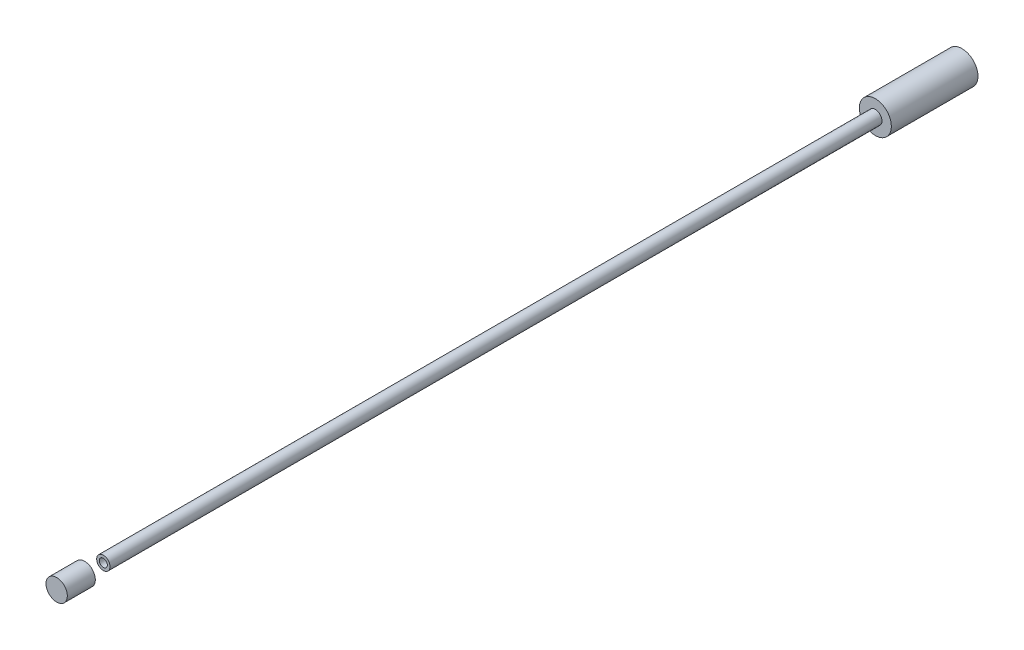
SolidWorks part; units mm, degrees
material "AISI 316 Annealed Stainless Steel Bar (SS)"
ref_plane "Front Plane" through (0, 0, 0) normal (0, 0, 1) x (1, 0, 0)
ref_plane "Top Plane" through (0, 0, 0) normal (0, 1, 0) x (1, 0, 0)
ref_plane "Right Plane" through (0, 0, 0) normal (1, 0, 0) x (0, 0, -1)
sketch "Extrude sketch 1" plane through (0, 0, 0) normal (0, 0, 1) x (1, 0, 0)
  circle A0 centre (285, 0) radius 12
  dimension "D1" = 24
extrude "Extrude 1" add sketch "Extrude sketch 1" along normal blind 65 from offset 335 separate body
sketch "Extrude sketch 2" plane through (0, 0, 0) normal (0, 0, 1) x (1, 0, 0)
  circle A0 centre (285, 0) radius 5
  circle A1 centre (285, 0) radius 3
  dimension "D1" = 6
  dimension "D2" = 10
extrude "Extrude 2" add sketch "Extrude sketch 2" along normal blind 579 from offset 270 separate body
sketch "Extrude sketch 3" plane through (0, 0, 0) normal (0, 0, 1) x (1, 0, 0)
  circle A0 centre (285, 0) radius 8
  dimension "D1" = 16
extrude "Extrude 3" add sketch "Extrude sketch 3" along normal blind 21 from offset 323 separate body
